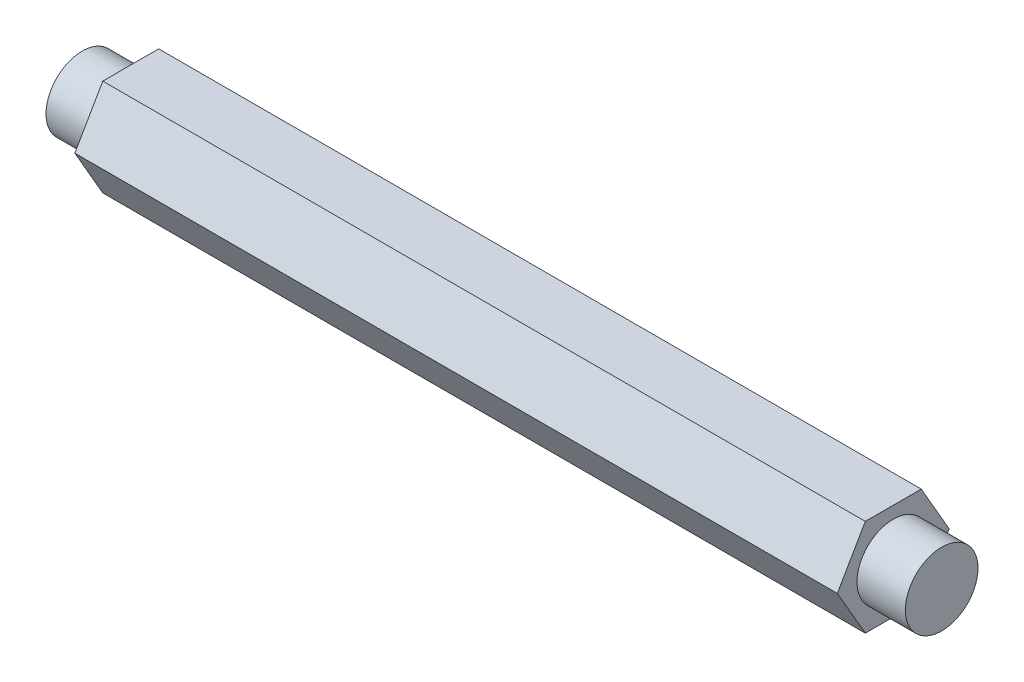
SolidWorks part; units mm, degrees
ref_plane "Alzado" through (0, 0, 0) normal (0, 0, 1) x (1, 0, 0)
ref_plane "Planta" through (0, 0, 0) normal (0, 1, 0) x (1, 0, 0)
ref_plane "Vista lateral" through (0, 0, 0) normal (1, 0, 0) x (0, 0, -1)
sketch "Croquis1" plane through (0, 0, 0) normal (1, 0, 0) x (0, 0, -1)
  line L1 (7.3323, 0) -> (3.6662, 6.35)
  line L2 (3.6662, 6.35) -> (-3.6662, 6.35)
  line L3 (-3.6662, 6.35) -> (-7.3323, 0)
  line L4 (-7.3323, 0) -> (-3.6662, -6.35)
  line L5 (-3.6662, -6.35) -> (3.6662, -6.35)
  line L6 (3.6662, -6.35) -> (7.3323, 0)
  circle A0 centre (0, 0) radius 6.35 construction
  dimension "D1" = 12.7
extrude "Saliente-Extruir1" add sketch "Croquis1" along normal blind 112.7
sketch "Croquis2" plane through (112.7, 0, 0) normal (1, 0, 0) x (0, 0, -1)
  circle A0 centre (0, 0) radius 7.3323
  circle A1 centre (0, 0) radius 4.7625
  dimension "D1" = 9.525
extrude "Cortar-Extruir1" cut sketch "Croquis2" against normal blind 6.35
sketch "Croquis3" plane through (0, 0, 0) normal (-1, 0, 0) x (0, 0, 1)
  circle A0 centre (0, 0) radius 7.3323
  circle A1 centre (0, 0) radius 4.7625
  dimension "D1" = 9.525
extrude "Cortar-Extruir2" cut sketch "Croquis3" against normal blind 6.35
